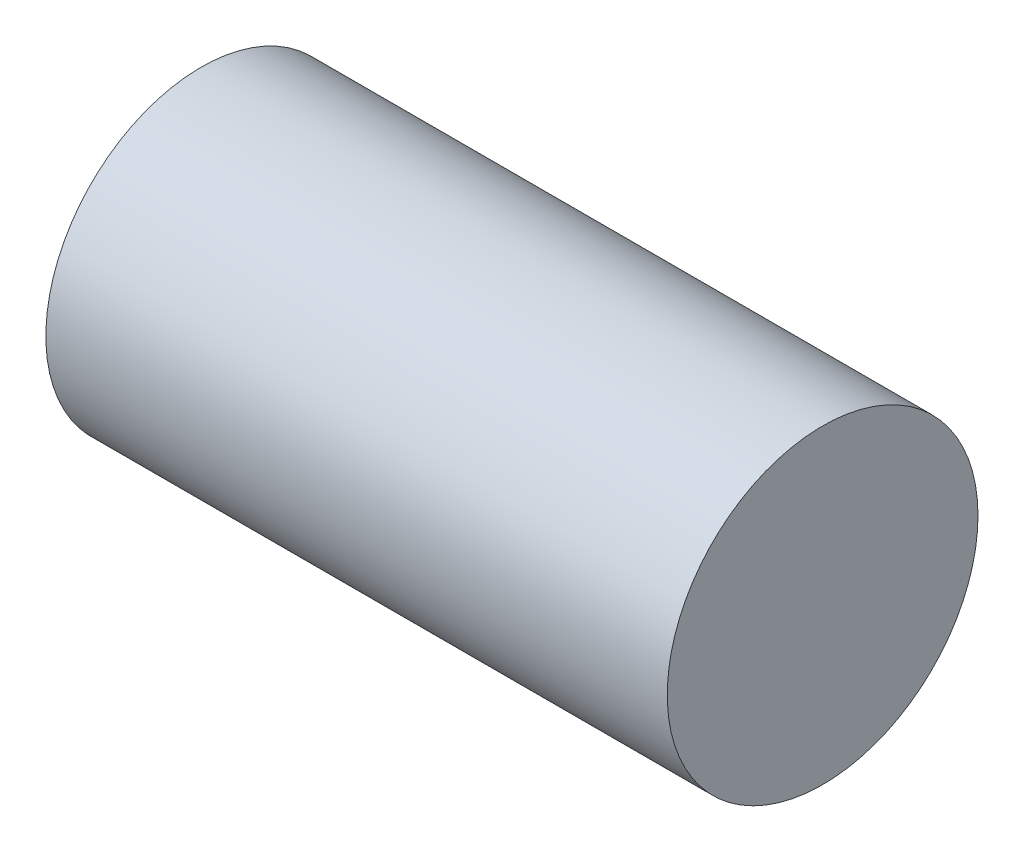
SolidWorks part; units mm, degrees
ref_plane "Ebene vorne" through (0, 0, 0) normal (0, 0, 1) x (1, 0, 0)
ref_plane "Ebene oben" through (0, 0, 0) normal (0, 1, 0) x (1, 0, 0)
ref_plane "Ebene rechts" through (0, 0, 0) normal (1, 0, 0) x (0, 0, -1)
sketch "Skizze2" plane through (0, 0, 0) normal (1, 0, 0) x (0, 0, -1)
  circle A0 centre (0, 0) radius 100
  dimension "D2" = 200
extrude "Aufsatz-Linear austragen1" add sketch "Skizze2" along normal blind 400
